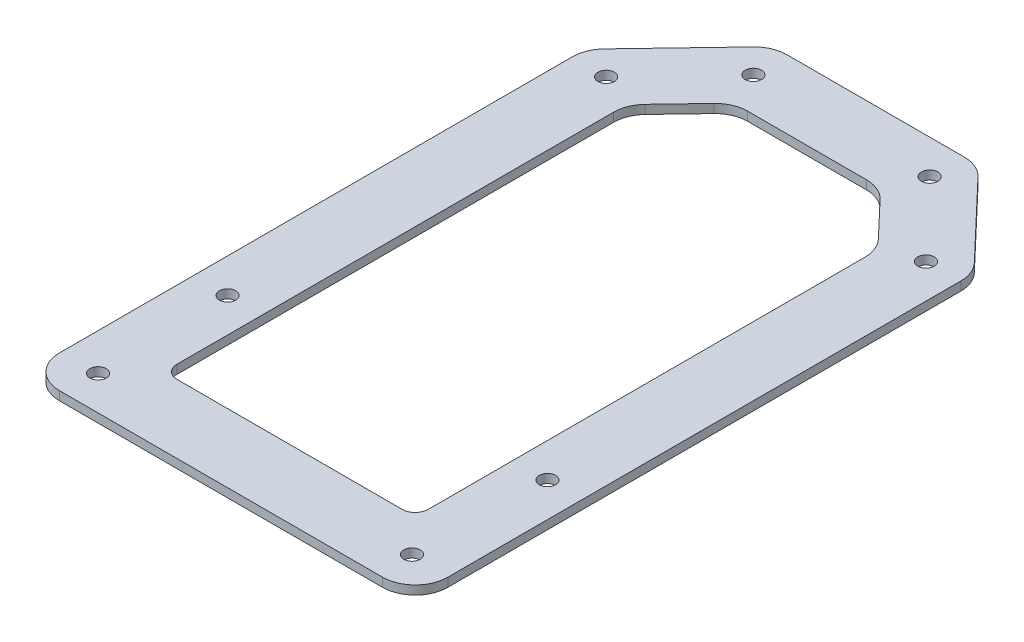
SolidWorks part; units mm, degrees
ref_plane "Front Plane" through (0, 0, 0) normal (0, 0, 1) x (1, 0, 0)
ref_plane "Top Plane" through (0, 0, 0) normal (0, 1, 0) x (1, 0, 0)
ref_plane "Right Plane" through (0, 0, 0) normal (1, 0, 0) x (0, 0, -1)
sketch "Sketch2" plane through (0, 0, 0) normal (0, 1, 0) x (1, 0, 0)
  circle A0 centre (-24.5, -29.84) radius 1.25 construction
  circle A1 centre (24.5, -29.84) radius 1.25 construction
  circle A2 centre (-24.5, 28.16) radius 1.25 construction
  circle A3 centre (24.5, 28.16) radius 1.25 construction
  circle A4 centre (-24.5, -29.84) radius 1.25
  circle A5 centre (24.5, -29.84) radius 1.25
  circle A6 centre (-24.5, 28.16) radius 1.25
  circle A7 centre (24.5, 28.16) radius 1.25
  circle A8 centre (-13.485, 39.7) radius 1.35 construction
  circle A9 centre (13.515, 39.7) radius 1.35 construction
  circle A10 centre (-24.085, -50.1) radius 1.35 construction
  circle A11 centre (24.015, -50.1) radius 1.35 construction
  circle A12 centre (-13.485, 39.7) radius 1.35
  circle A13 centre (13.515, 39.7) radius 1.35
  circle A14 centre (-24.085, -50.1) radius 1.35
  circle A15 centre (24.015, -50.1) radius 1.35
  point P25 (-13.485, 39.7)
  point P26 (-24.085, -50.1)
  point P27 (24.015, -50.1)
  point P28 (13.515, 39.7)
sketch "Sketch3" plane through (0, 0, 0) normal (0, 1, 0) x (1, 0, 0)
  line L0 (13.515, 40.95) -> (13.515, 44.95) construction
  line L1 (-29.75, 44.95) -> (29.75, 44.95) construction
  line L2 (-29.75, 44.95) -> (-29.75, -55.35) construction
  line L3 (-29.75, -55.35) -> (29.75, -55.35)
  line L4 (29.75, 44.95) -> (29.75, -55.35) construction
  line L5 (-25.75, 28.16) -> (-29.75, 28.16) construction
  line L6 (25.75, 28.16) -> (29.75, 28.16) construction
  line L7 (24.015, -51.35) -> (24.015, -55.35) construction
  line L8 (-13.485, 38.45) -> (-13.485, 34.45) construction
  line L9 (-19.25, 34.45) -> (19.25, 34.45) construction
  line L10 (-19.25, 34.45) -> (-19.25, -44.85) construction
  line L11 (-19.25, -44.85) -> (19.25, -44.85)
  line L12 (19.25, 34.45) -> (19.25, -44.85) construction
  line L13 (-24.085, -48.85) -> (-24.085, -44.85) construction
  line L14 (-23.25, -29.84) -> (-19.25, -29.84) construction
  line L15 (23.25, -29.84) -> (19.25, -29.84) construction
  line L16 (-24.5, 28.16) -> (-13.485, 39.7) construction
  line L17 (13.515, 39.7) -> (24.5, 28.16) construction
  line L18 (-29.75, 30.2634) -> (-15.7315, 44.95)
  line L19 (15.7516, 44.95) -> (29.75, 30.2443)
  line L20 (-19.25, 26.0566) -> (-11.2385, 34.45)
  line L21 (11.2499, 34.45) -> (19.25, 26.0457)
  line L22 (-28.2977, 31.7849) -> (-25.4042, 29.0231) construction
  line L23 (-9.6873, 36.0751) -> (-12.5808, 38.8369) construction
  line L24 (-15.7315, 44.95) -> (15.7516, 44.95)
  line L25 (-11.2385, 34.45) -> (11.2499, 34.45)
  line L26 (-29.75, 30.2634) -> (-29.75, -55.35)
  line L27 (-19.25, 26.0566) -> (-19.25, -44.85)
  line L28 (19.25, 26.0457) -> (19.25, -44.85)
  line L29 (29.75, 30.2443) -> (29.75, -55.35)
  circle A0 centre (13.515, 39.7) radius 1.25
  circle A1 centre (-13.485, 39.7) radius 1.25
  circle A2 centre (-24.5, 28.16) radius 1.25
  circle A3 centre (-24.5, -29.84) radius 1.25
  circle A4 centre (-24.085, -50.1) radius 1.25
  circle A5 centre (24.5, -29.84) radius 1.25
  circle A6 centre (24.015, -50.1) radius 1.25
  circle A7 centre (24.5, 28.16) radius 1.25
  point P24 (13.515, 40.95)
  point P25 (-25.75, 28.16)
  point P26 (25.75, 28.16)
  point P27 (24.015, -51.35)
  point P28 (-24.085, -48.85)
  point P29 (-13.485, 38.45)
  point P30 (-23.25, -29.84)
  dimension "D1" = 2.5
  dimension "D2" = 4
extrude "Boss-Extrude1" add sketch "Sketch3" against normal blind 1.35
fillet "Fillet1" radius 5 10 edges at (19.25, -0.675, -26.0457) (11.2499, -0.675, -34.45) (-11.2385, -0.675, -34.45) (-19.25, -0.675, -26.0566) (-29.75, -0.675, -30.2634) (-15.7315, -0.675, -44.95) (15.7516, -0.675, -44.95) (29.75, -0.675, -30.2443) (29.75, -0.675, 55.35) (-29.75, -0.675, 55.35)
fillet "Fillet2" radius 2 2 edges at (19.25, -0.675, 44.85) (-19.25, -0.675, 44.85)
equation "\"Black_acrylic\"= 1.35mm"
equation "\"MDF_base\"= 20mm"
equation "\"Supports_material\"= 5.4mm"
equation "\"D1@Boss-Extrude1\"=\"Black_acrylic\""
